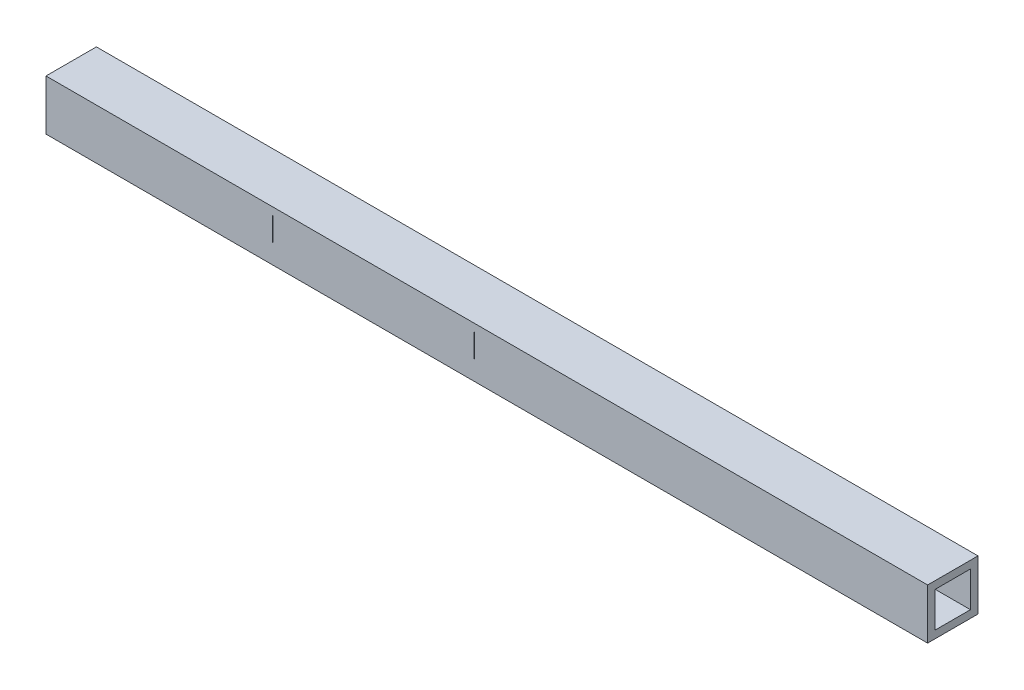
SolidWorks part; units mm, degrees
ref_plane "Alzado" through (0, 0, 0) normal (0, 0, 1) x (1, 0, 0)
ref_plane "Planta" through (0, 0, 0) normal (0, 1, 0) x (1, 0, 0)
ref_plane "Vista lateral" through (0, 0, 0) normal (1, 0, 0) x (0, 0, -1)
ref_plane "Plano1" through (0, -5, 0) normal (0, -1, 0) x (1, 0, 0)
sketch "Croquis1" plane through (0, -5, 0) normal (0, -1, 0) x (1, 0, 0)
  line L0 (0, 5) -> (0, -5)
  line L1 (0, -5) -> (175, -5)
  line L2 (175, -5) -> (175, 5)
  line L3 (175, 5) -> (0, 5)
  dimension "D1" = 175
extrude "Saliente-Extruir1" add sketch "Croquis1" against normal blind 10
sketch "Croquis2" plane through (0, 0, 0) normal (-1, 0, 0) x (0, 0, 1)
  line L0 (3.5, 3.5) -> (-3.5, 3.5)
  line L1 (-3.5, 3.5) -> (-3.5, -3.5)
  line L2 (-3.5, -3.5) -> (3.5, -3.5)
  line L3 (3.5, -3.5) -> (3.5, 3.5)
extrude "Cortar-Extruir1" cut sketch "Croquis2" against normal through all
sketch "Croquis3" plane through (0, 0, 5) normal (0, 0, 1) x (1, 0, 0)
  line L0 (25.01, -1.1667) -> (25.01, 3.5)
  line L1 (25.01, 3.5) -> (24.99, 3.5)
  line L2 (24.99, 3.5) -> (24.99, -1.1667)
  line L3 (24.99, -1.1667) -> (25.01, -1.1667)
extrude "Cortar-Extruir2" cut sketch "Croquis3" against normal blind 0.02
sketch "Croquis4" plane through (0, 0, 5) normal (0, 0, 1) x (1, 0, 0)
  line L0 (35.01, -1.1667) -> (35.01, 3.5)
  line L1 (35.01, 3.5) -> (34.99, 3.5)
  line L2 (34.99, 3.5) -> (34.99, -1.1667)
  line L3 (34.99, -1.1667) -> (35.01, -1.1667)
extrude "Cortar-Extruir3" cut sketch "Croquis4" against normal blind 0.02
sketch "Croquis5" plane through (0, 0, 5) normal (0, 0, 1) x (1, 0, 0)
  line L0 (45.01, -1.1667) -> (45.01, 3.5)
  line L1 (45.01, 3.5) -> (44.99, 3.5)
  line L2 (44.99, 3.5) -> (44.99, -1.1667)
  line L3 (44.99, -1.1667) -> (45.01, -1.1667)
extrude "Cortar-Extruir4" cut sketch "Croquis5" against normal blind 0.02
sketch "Croquis6" plane through (0, 0, 5) normal (0, 0, 1) x (1, 0, 0)
  line L0 (55.01, -1.1667) -> (55.01, 3.5)
  line L1 (55.01, 3.5) -> (54.99, 3.5)
  line L2 (54.99, 3.5) -> (54.99, -1.1667)
  line L3 (54.99, -1.1667) -> (55.01, -1.1667)
extrude "Cortar-Extruir5" cut sketch "Croquis6" against normal blind 0.02
sketch "Croquis7" plane through (0, 0, 5) normal (0, 0, 1) x (1, 0, 0)
  line L0 (65.01, -1.1667) -> (65.01, 3.5)
  line L1 (65.01, 3.5) -> (64.99, 3.5)
  line L2 (64.99, 3.5) -> (64.99, -1.1667)
  line L3 (64.99, -1.1667) -> (65.01, -1.1667)
extrude "Cortar-Extruir6" cut sketch "Croquis7" against normal blind 0.02
sketch "Croquis8" plane through (0, 0, 5) normal (0, 0, 1) x (1, 0, 0)
  line L0 (75.01, -1.1667) -> (75.01, 3.5)
  line L1 (75.01, 3.5) -> (74.99, 3.5)
  line L2 (74.99, 3.5) -> (74.99, -1.1667)
  line L3 (74.99, -1.1667) -> (75.01, -1.1667)
extrude "Cortar-Extruir7" cut sketch "Croquis8" against normal blind 0.02
sketch "Croquis9" plane through (0, 0, 5) normal (0, 0, 1) x (1, 0, 0)
  line L0 (85.01, -1.1667) -> (85.01, 3.5)
  line L1 (85.01, 3.5) -> (84.99, 3.5)
  line L2 (84.99, 3.5) -> (84.99, -1.1667)
  line L3 (84.99, -1.1667) -> (85.01, -1.1667)
extrude "Cortar-Extruir8" cut sketch "Croquis9" against normal blind 0.02
sketch "Croquis10" plane through (0, 0, 5) normal (0, 0, 1) x (1, 0, 0)
  line L0 (15.01, -1.1667) -> (15.01, 3.5)
  line L1 (15.01, 3.5) -> (14.99, 3.5)
  line L2 (14.99, 3.5) -> (14.99, -1.1667)
  line L3 (14.99, -1.1667) -> (15.01, -1.1667)
extrude "Cortar-Extruir9" cut sketch "Croquis10" against normal blind 0.02
